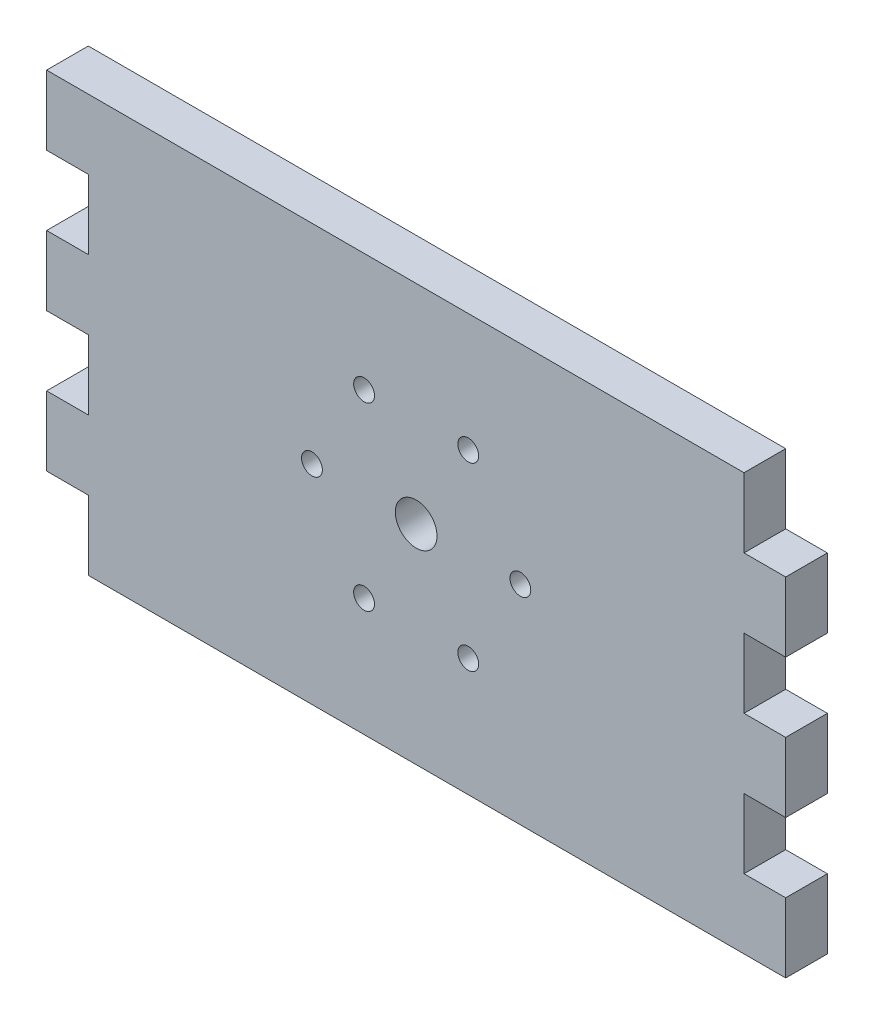
SolidWorks part; units mm, degrees
ref_plane "Alzado" through (0, 0, 0) normal (0, 0, 1) x (1, 0, 0)
ref_plane "Planta" through (0, 0, 0) normal (0, 1, 0) x (1, 0, 0)
ref_plane "Vista lateral" through (0, 0, 0) normal (1, 0, 0) x (0, 0, -1)
sketch "Croquis1" plane through (0, 0, 0) normal (0, 0, 1) x (1, 0, 0)
  line L0 (26.6, 5) -> (26.6, 10)
  line L1 (-23.6, -15) -> (26.6, -15)
  line L2 (-26.6, -10) -> (-26.6, -5)
  line L3 (-26.6, 15) -> (23.6, 15)
  line L4 (26.6, -15) -> (26.6, -10)
  line L5 (-26.6, -15) -> (26.6, 15) construction
  line L6 (-26.6, 15) -> (26.6, -15) construction
  line L7 (23.6, -10) -> (26.6, -10)
  line L8 (23.6, -10) -> (23.6, -5)
  line L9 (23.6, -5) -> (26.6, -5)
  line L11 (23.6, -10) -> (26.6, -5) construction
  line L12 (23.6, -5) -> (26.6, -10) construction
  line L13 (23.6, 0) -> (26.6, 0)
  line L14 (23.6, 0) -> (23.6, 5)
  line L15 (23.6, 5) -> (26.6, 5)
  line L16 (26.6, -5) -> (26.6, 0)
  line L17 (23.6, 0) -> (26.6, 5) construction
  line L18 (23.6, 5) -> (26.6, 0) construction
  line L19 (23.6, 10) -> (26.6, 10)
  line L20 (23.6, 10) -> (23.6, 15)
  line L21 (-23.6, -15) -> (-23.6, -10)
  line L22 (-26.6, 10) -> (-26.6, 15)
  line L23 (23.6, 10) -> (26.6, 15) construction
  line L24 (23.6, 15) -> (26.6, 10) construction
  line L25 (0, -15) -> (0, 15) construction
  line L28 (-23.6, 5) -> (-23.6, 10)
  line L29 (-23.6, 10) -> (-26.6, 10)
  line L30 (-26.6, 0) -> (-26.6, 5)
  line L31 (-23.6, 5) -> (-26.6, 5)
  line L33 (-23.6, 0) -> (-26.6, 0)
  line L35 (-23.6, -5) -> (-26.6, -5)
  line L37 (-23.6, -10) -> (-26.6, -10)
  line L38 (-26.6, -15) -> (-26.6, 15) construction
  line L39 (26.6, 15) -> (26.6, -15) construction
  line L41 (-26.6, -15) -> (26.6, -15) construction
  line L42 (-23.6, -5) -> (-23.6, 0)
  point P0 (0, 0)
  point P6 (25.1, -7.5)
  point P11 (25.1, 2.5)
  point P16 (25.1, 12.5)
  dimension "D1" = 53.2
  dimension "D2" = 30
  dimension "D3" = 3
  dimension "D4" = 5
  dimension "D5" = 5
  dimension "D6" = 5
extrude "Saliente-Extruir1" add sketch "Croquis1" along normal blind 3
sketch "Croquis2" plane through (0, 0, 3) normal (0, 0, 1) x (1, 0, 0)
  line L0 (0, -15) -> (0, 15) construction
  line L1 (-23.6, -15) -> (26.6, -15) construction
  line L2 (23.6, 15) -> (-26.6, 15) construction
  line L3 (-25.1, 0) -> (26.6, 0) construction
  line L4 (-26.6, 0) -> (-23.6, 0) construction
  circle A0 centre (0, 0) radius 1.5
  circle A1 centre (7.5, 0) radius 0.75
  circle A2 centre (3.75, -6.4952) radius 0.75
  circle A3 centre (-3.75, -6.4952) radius 0.75
  circle A4 centre (-7.5, 0) radius 0.75
  circle A5 centre (-3.75, 6.4952) radius 0.75
  circle A6 centre (3.75, 6.4952) radius 0.75
  point P17 (0, 0)
  point P18 (0, 0)
  point P28 (0, 0)
  point P29 (0, 0)
  point P30 (0, 0)
  point P31 (0, 0)
  dimension "D1" = 3
  dimension "D2" = 1.5
  dimension "D3" = 7.5
  dimension "D4" = 6
extrude "Cortar-Extruir1" cut sketch "Croquis2" against normal up to next
